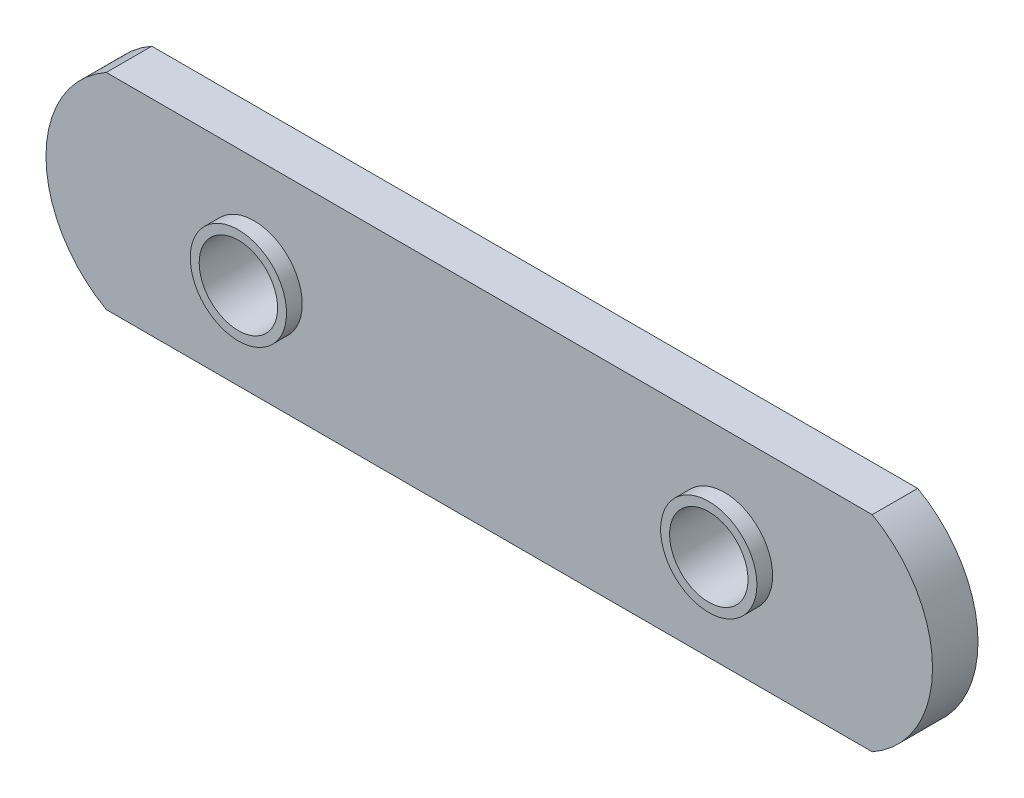
SolidWorks part; units mm, degrees
material "Plain Carbon Steel"
ref_plane "Front Plane" through (0, 0, 0) normal (0, 0, 1) x (1, 0, 0)
ref_plane "Top Plane" through (0, 0, 0) normal (0, 1, 0) x (1, 0, 0)
ref_plane "Right Plane" through (0, 0, 0) normal (1, 0, 0) x (0, 0, -1)
sketch "Sketch1" plane through (0, 0, 0) normal (0, 0, 1) x (1, 0, 0)
  line L0 (-31.0177, 8.3185) -> (31.0177, 8.3185)
  line L2 (31.0177, -8.3185) -> (-31.0177, -8.3185)
  line L4 (35.9029, 0) -> (-35.9029, 0) construction
  arc A0 (31.0177, -8.3185) -> (31.0177, 8.3185) centre (26.3779, 0) ccw
  arc A1 (-31.0177, 8.3185) -> (-31.0177, -8.3185) centre (-26.3779, 0) ccw
  dimension "D3" = 19.05
  dimension "D1" = 19.05
  dimension "D2" = 16.637
  dimension "D4" = 71.8058
extrude "Boss-Extrude1" add sketch "Sketch1" along normal mid plane 3.683
sketch "Sketch2" plane through (0, 0, 1.8415) normal (0, 0, 1) x (1, 0, 0)
  circle A0 centre (19.05, 0) radius 3.8989
  circle A1 centre (-19.05, 0) radius 3.8989
  dimension "D3" = 7.7978
  dimension "D1" = 38.1
  dimension "D2" = 19.05
extrude "Boss-Extrude2" add sketch "Sketch2" along normal blind 1.27
hole_wizard "1/4-20 Tapped Hole1" positions "Sketch5" profile "Sketch4" tap size "1/4-20" standard "Ansi Inch"
sketch "Sketch5" plane through (0, 0, -1.8415) normal (0, 0, -1) x (-1, 0, 0)
  line L0 (19.05, 0) -> (0, 0) construction
  line L2 (-19.05, 0) -> (0, 0) construction
  point P1 (19.05, 0)
  point P3 (-19.05, 0)
  dimension "D1" = 38.1
  dimension "D2" = 19.05
sketch "Sketch4" plane through (-19.05, 0, -1.8415) normal (1, 0, 0) x (0, 1, 0)
  line L0 (0, 0) -> (0, 18.0438)
  line L1 (0, 18.0438) -> (2.5527, 16.51)
  line L2 (2.5527, 16.51) -> (2.5527, 12.7)
  line L3 (2.5527, 12.7) -> (3.175, 12.7)
  line L4 (3.175, 12.7) -> (3.175, 0)
  line L5 (3.175, 0) -> (0, 0)
  line L10 (0, 18.0438) -> (-2.5527, 16.51) construction
  line L11 (0, -6.35) -> (0, 107.95) construction
  dimension "Tap Drill Dia." = 5.1054
  dimension "Tap Drill Depth" = 16.51
  dimension "Thread Major Dia." = 6.35
  dimension "Thread Depth" = 12.7
  dimension "Drill Angle" = 118
